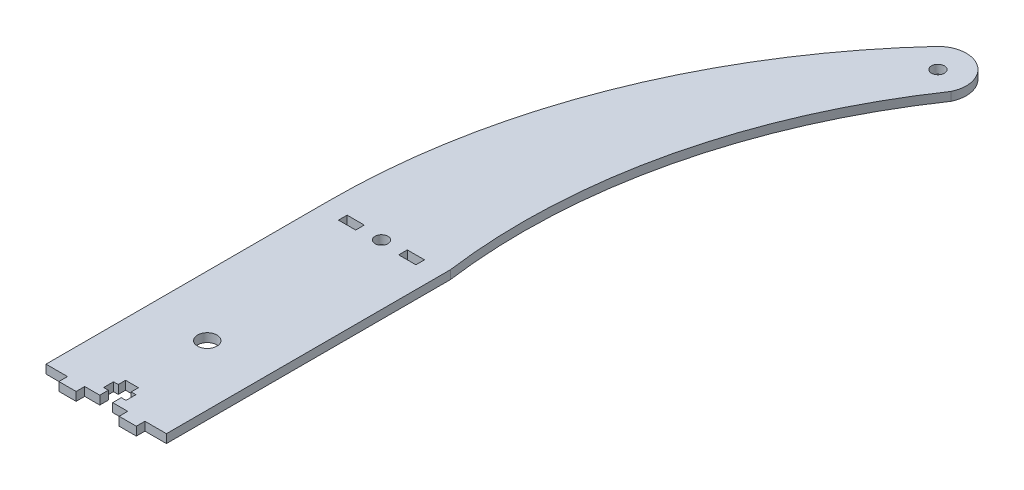
SolidWorks part; units mm, degrees
ref_plane "Front Plane" through (0, 0, 0) normal (0, 0, 1) x (1, 0, 0)
ref_plane "Top Plane" through (0, 0, 0) normal (0, 1, 0) x (1, 0, 0)
ref_plane "Right Plane" through (0, 0, 0) normal (1, 0, 0) x (0, 0, -1)
sketch "Sketch1" plane through (0, 0, 0) normal (0, 1, 0) x (1, 0, 0)
  line L0 (0, 33) -> (28, 33) construction
  line L1 (0, 0) -> (5, 0)
  line L2 (0, 0) -> (0, 66)
  line L3 (0, 66) -> (28, 66)
  line L4 (28, 0) -> (28, 66)
  line L5 (14, 66) -> (14, 0) construction
  line L6 (14, 57.25) -> (18.75, 57.25) construction
  line L13 (5, 0) -> (5, -2)
  line L19 (12.5, 6) -> (15.5, 6)
  line L20 (12.5, 6) -> (12.5, 4.3)
  line L33 (15.5, 6) -> (15.5, 4.3)
  line L34 (12.5, 6) -> (15.5, 0) construction
  line L35 (12.5, 0) -> (15.5, 6) construction
  line L36 (15.5, 2) -> (16.6, 2)
  line L38 (15.5, 4.3) -> (16.6, 4.3)
  line L39 (16.6, 2) -> (16.6, 4.3)
  line L41 (19, 0) -> (19, -2)
  line L42 (19, -2) -> (23, -2)
  line L43 (23, 0) -> (23, -2)
  line L44 (9, -2) -> (5, -2)
  line L45 (9, 0) -> (9, -2)
  line L46 (12.5, 2) -> (11.4, 2)
  line L47 (11.4, 2) -> (11.4, 4.3)
  line L48 (12.5, 4.3) -> (11.4, 4.3)
  line L49 (9, 0) -> (12.5, 0)
  line L50 (23, 0) -> (28, 0)
  line L51 (12.5, 2) -> (12.5, 0)
  line L52 (15.5, 2) -> (15.5, 0)
  line L53 (15.5, 0) -> (19, 0)
  line L54 (14, 64) -> (21, 64) construction
  line L55 (5, 65) -> (9, 65)
  line L56 (23, 63) -> (19, 63)
  line L57 (23, 63) -> (23, 65)
  line L58 (23, 65) -> (19, 65)
  line L59 (19, 63) -> (19, 65)
  line L60 (23, 63) -> (19, 65) construction
  line L61 (23, 65) -> (19, 63) construction
  line L62 (9, 63) -> (9, 65)
  line L63 (5, 63) -> (9, 63)
  line L64 (5, 63) -> (5, 65)
  circle A6 centre (14, 64) radius 1.5
  circle A7 centre (14, 23.49) radius 2.25
  point P9 (14, 33)
  point P12 (14, 22.7501)
  point P23 (14, 3)
  point P36 (19, -1)
  dimension "D8" = 5
  dimension "D18" = 3
  dimension "D3" = 4.5
  dimension "D4" = 9.51
  dimension "D1" = 28
  dimension "D2" = 66
  dimension "D6" = 4.75
  dimension "D9" = 4
  dimension "D10" = 2
  dimension "D11" = 3
  dimension "D12" = 6
  dimension "D13" = 1.1
  dimension "D14" = 2.3
  dimension "D15" = 2
  dimension "D16" = 4
  dimension "D17" = 2
  dimension "D19" = 5
  dimension "D20" = 1
extrude "Boss-Extrude1" add sketch "Sketch1" along normal blind 2
sketch "Sketch2" plane through (0, 2, 0) normal (0, 1, 0) x (1, 0, 0)
  line L0 (0, 66) -> (150, 66) construction
  line L1 (150, 66) -> (28, 66) construction
  line L2 (0, 66) -> (161.7933, 84.01) construction
  line L3 (161.7933, 84.01) -> (28, 66) construction
  line L4 (64.776, 189.4377) -> (70.3785, 183.3496) construction
  line L5 (0, 66) -> (28, 66)
  arc A0 (64.776, 189.4377) -> (0, 66) centre (150, 66) ccw
  arc A1 (70.3785, 183.3496) -> (28, 66) centre (161.7933, 84.01) ccw
  arc A2 (64.776, 189.4377) -> (70.3785, 183.3496) centre (67.1495, 186) cw
  point P6 (64.776, 189.4377)
  point P8 (125.0223, 213.9058)
  dimension "D1" = 300
  dimension "D2" = 270
  dimension "D3" = 120
extrude "Boss-Extrude2" add sketch "Sketch2" against normal blind 2
sketch "Sketch4" plane through (0, 2, 0) normal (0, 1, 0) x (1, 0, 0)
  line L0 (39.4544, 167.3888) -> (49.2781, 158.6112) construction
  line L2 (49.2781, 158.6112) -> (90.3366, 196.3334)
  line L3 (90.3366, 196.3334) -> (75.55, 212.4278)
  line L4 (75.55, 212.4278) -> (35.4691, 175.6037)
  line L5 (35.4691, 175.6037) -> (39.4544, 167.3888)
  line L6 (19, 63) -> (23, 63) construction
  arc A0 (64.776, 189.4377) -> (0, 66) centre (150, 66) ccw construction
  arc A1 (70.3785, 183.3496) -> (28, 66) centre (161.7933, 84.01) ccw construction
  circle A2 centre (44.3663, 163) radius 1.5
  arc A3 (39.4544, 167.3888) -> (49.2781, 158.6112) centre (44.3663, 163) cw
  dimension "D1" = 3
  dimension "D2" = 100
extrude "Cut-Extrude1" cut sketch "Sketch4" against normal blind 2
